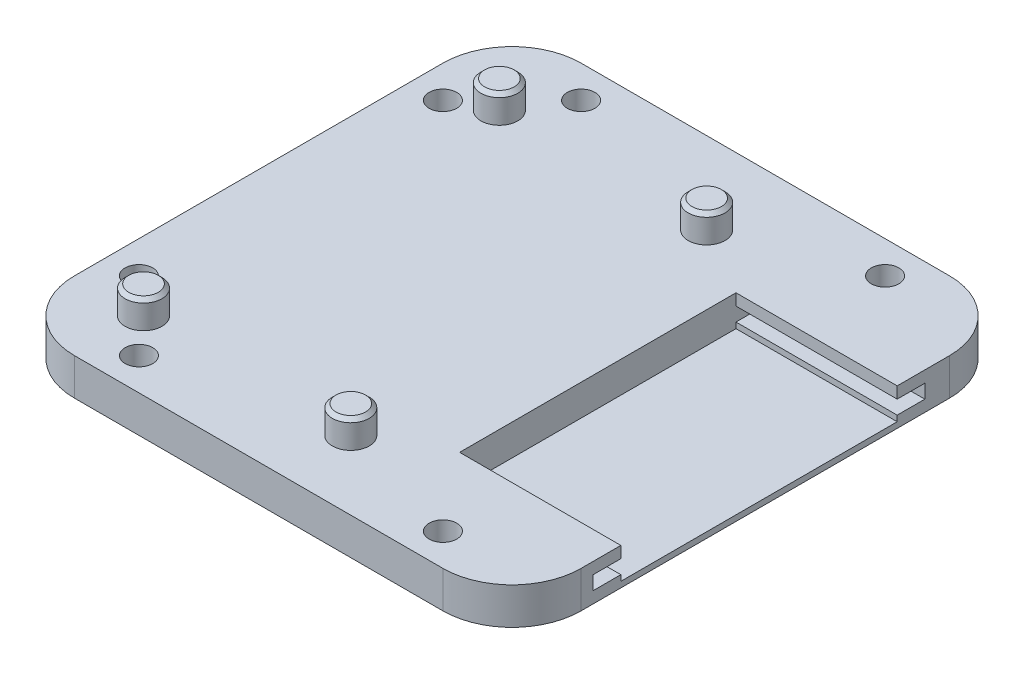
SolidWorks part; units mm, degrees
ref_plane "Front Plane" through (0, 0, 0) normal (0, 0, 1) x (1, 0, 0)
ref_plane "Top Plane" through (0, 0, 0) normal (0, 1, 0) x (1, 0, 0)
ref_plane "Right Plane" through (0, 0, 0) normal (1, 0, 0) x (0, 0, -1)
sketch "Sketch1" plane through (0, 0, 0) normal (0, 1, 0) x (1, 0, 0)
  line L0 (39.6261, 56.371) -> (-40.3739, 56.371)
  line L1 (-55.3739, 41.371) -> (-55.3739, -38.629)
  line L2 (-40.3739, -53.629) -> (39.6261, -53.629)
  line L3 (54.6261, -38.629) -> (54.6261, 41.371)
  circle A0 centre (-48.3739, 34.371) radius 3
  circle A1 centre (-33.3739, 49.371) radius 3
  arc A2 (54.6261, 41.371) -> (39.6261, 56.371) centre (39.6261, 41.371) ccw
  arc A3 (-40.3739, 56.371) -> (-55.3739, 41.371) centre (-40.3739, 41.371) ccw
  arc A4 (-55.3739, -38.629) -> (-40.3739, -53.629) centre (-40.3739, -38.629) ccw
  arc A5 (39.6261, -53.629) -> (54.6261, -38.629) centre (39.6261, -38.629) ccw
  circle A6 centre (32.6261, 49.371) radius 3
  circle A8 centre (-48.3739, -31.629) radius 3
  circle A9 centre (-33.3739, -46.629) radius 3
  circle A10 centre (32.6261, -46.629) radius 3
extrude "Boss-Extrude1" add sketch "Sketch1" along normal blind 8
sketch "Sketch3" plane through (54.6261, 0, 0) normal (1, 0, 0) x (0, 0, -1)
  line L0 (-30, 8) -> (-30, 5.5)
  line L1 (-38.629, 8) -> (41.371, 8) construction
  line L2 (-30, 5.5) -> (-36, 5.5)
  line L3 (-36, 5.5) -> (-36, 2.5)
  line L4 (-36, 2.5) -> (-30, 2.5)
  line L5 (-30, 2.5) -> (-30, 1.25)
  line L7 (0, 0) -> (0, 8) construction
  line L8 (30, 2.5) -> (30, 1.25)
  line L9 (36, 2.5) -> (30, 2.5)
  line L10 (36, 5.5) -> (36, 2.5)
  line L11 (30, 5.5) -> (36, 5.5)
  line L12 (30, 8) -> (30, 5.5)
  line L13 (-30, 8) -> (30, 8)
  line L15 (-30, 1.25) -> (30, 1.25)
  dimension "D1" = 30
  dimension "D2" = 30
  dimension "D3" = 6
  dimension "D4" = 3
  dimension "D5" = 2.5
extrude "Cut-Extrude1" cut sketch "Sketch3" against normal blind 35
sketch "Sketch4" plane through (0, 8, 0) normal (0, 1, 0) x (1, 0, 0)
  line L0 (-40.3739, -53.629) -> (39.6261, -53.629) construction
  line L1 (-55.3739, 41.371) -> (-55.3739, -38.629) construction
  circle A0 centre (4.6261, -38.629) radius 4
  circle A1 centre (-40.3739, -38.629) radius 4
  point P4 (13.5244, -38.4669)
  dimension "D1" = 8
  dimension "D2" = 8
  dimension "D3" = 45
  dimension "D4" = 15
  dimension "D5" = 15
extrude "Boss-Extrude2" add sketch "Sketch4" along normal blind 6
chamfer "Chamfer1" distance 0.8 angle 45 2 edges at (4.6261, 14, 42.629) (-40.3739, 14, 42.629)
mirror "Mirror1" about plane through (0, 0, 0) normal (0, 0, 1) of "Chamfer1", "Boss-Extrude2"
